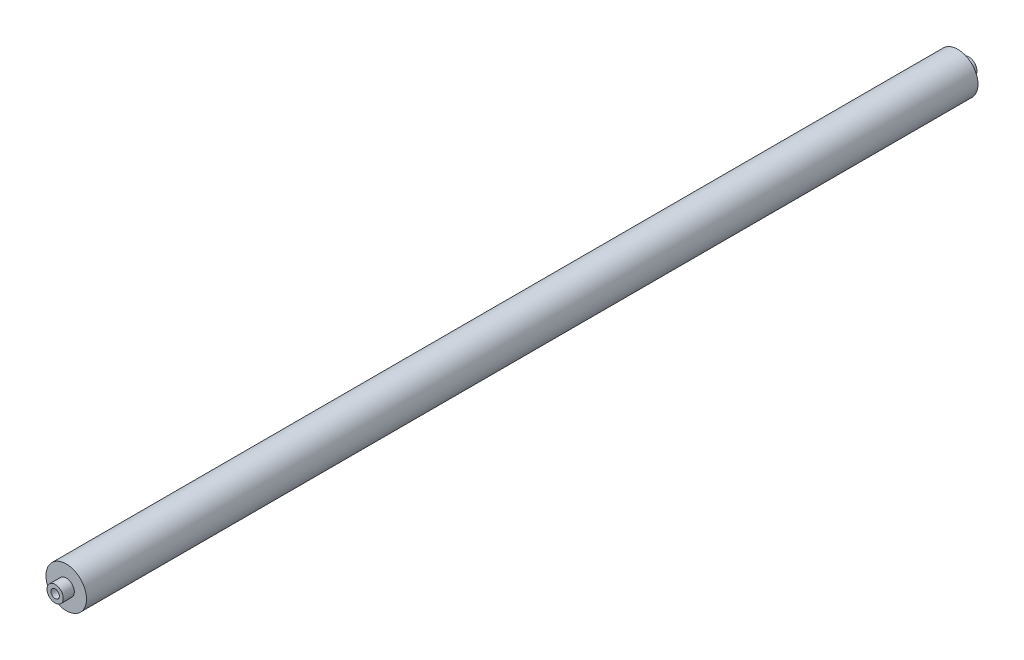
SolidWorks part; units mm, degrees
material "Pure Gold"
ref_plane "Front Plane" through (0, 0, 0) normal (0, 0, 1) x (1, 0, 0)
ref_plane "Top Plane" through (0, 0, 0) normal (0, 1, 0) x (1, 0, 0)
ref_plane "Right Plane" through (0, 0, 0) normal (1, 0, 0) x (0, 0, -1)
sketch "Sketch1" plane through (0, 0, 0) normal (0, 0, 1) x (1, 0, 0)
  circle A0 centre (0, 0) radius 15.875
  dimension "D1" = 31.75
extrude "Boss-Extrude1" add sketch "Sketch1" along normal blind 698.5 contours A0
sketch "Sketch2" plane through (0, 0, 698.5) normal (0, 0, 1) x (1, 0, 0)
  circle A0 centre (0, 0) radius 6.35
  dimension "D1" = 12.7
extrude "Boss-Extrude2" add sketch "Sketch2" along normal blind 12.7 contours A0
sketch "Sketch3" plane through (0, 0, 0) normal (0, 0, -1) x (-1, 0, 0)
  circle A0 centre (0, 0) radius 6.35
  dimension "D1" = 12.7
extrude "Boss-Extrude3" add sketch "Sketch3" along normal blind 12.7
sketch "Sketch6" plane through (0, 0, 711.2) normal (0, 0, 1) x (1, 0, 0)
  point P0 (0, 0)
  point P3 (0, 0)
hole_wizard "CBORE for M6 Hex Head1" positions "Sketch6" profile "Sketch7" counterbore size "M6" standard "BSI"
sketch "Sketch7" plane through (0, 0, 711.2) normal (1, 0, 0) x (0, -1, 0)
  line L0 (0, 0) -> (0, 306.7828)
  line L1 (0, 306.7828) -> (3.3, 304.8)
  line L2 (3.3, 304.8) -> (3.3, 4)
  line L3 (3.3, 4) -> (7.2735, 4)
  line L4 (7.2735, 4) -> (7.2735, 0)
  line L5 (7.2735, 0) -> (0, 0)
  line L10 (0, 306.7828) -> (-3.3, 304.8) construction
  line L11 (0, -6.35) -> (0, 107.95) construction
  dimension "Hole Dia." = 6.6
  dimension "Hole Depth" = 304.8
  dimension "C'Bore Dia." = 14.547
  dimension "C'Bore Depth" = 4
  dimension "Drill Angle" = 118
sketch "Sketch11" plane through (0, 0, -12.7) normal (0, 0, -1) x (-1, 0, 0)
  circle A0 centre (0, 0) radius 3.175
  circle A1 centre (0, 0) radius 6.35 construction
  point P0 (0, 0)
  dimension "D1" = 6.35
  dimension "D2" = 3.175
  dimension "D3" = 3.175
hole_wizard "CBORE for M6 Hex Head4" positions "Sketch11" profile "Sketch13" counterbore size "M6" standard "BSI"
sketch "Sketch13" plane through (0, 0, -12.7) normal (1, 0, 0) x (0, 1, 0)
  line L0 (0, 0) -> (0, 306.7828)
  line L1 (0, 306.7828) -> (3.3, 304.8)
  line L2 (3.3, 304.8) -> (3.3, 4)
  line L3 (3.3, 4) -> (7.2735, 4)
  line L4 (7.2735, 4) -> (7.2735, 0)
  line L5 (7.2735, 0) -> (0, 0)
  line L10 (0, 306.7828) -> (-3.3, 304.8) construction
  line L11 (0, -6.35) -> (0, 107.95) construction
  dimension "Hole Dia." = 6.6
  dimension "Hole Depth" = 304.8
  dimension "C'Bore Dia." = 14.547
  dimension "C'Bore Depth" = 4
  dimension "Drill Angle" = 118
